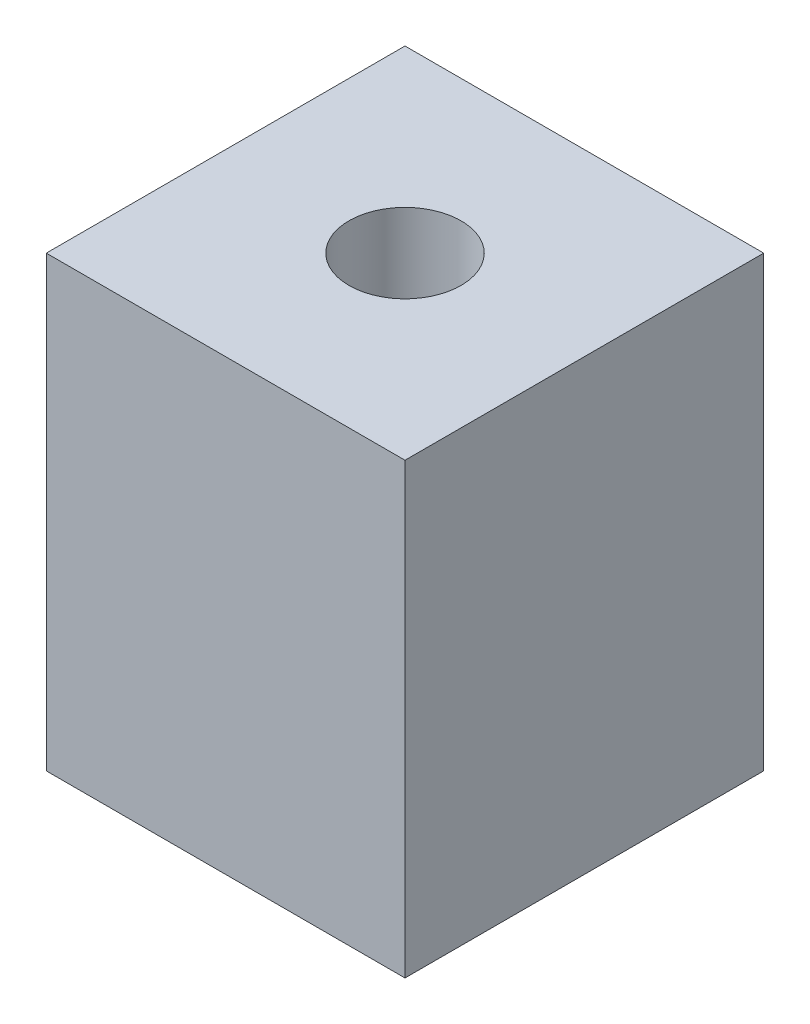
SolidWorks part; units mm, degrees
ref_plane "前基準面" through (0, 0, 0) normal (0, 0, 1) x (1, 0, 0)
ref_plane "上基準面" through (0, 0, 0) normal (0, 1, 0) x (1, 0, 0)
ref_plane "右基準面" through (0, 0, 0) normal (1, 0, 0) x (0, 0, -1)
sketch "草圖1" plane through (0, 0, 0) normal (0, 1, 0) x (1, 0, 0)
  circle A0 centre (0, 0) radius 6
  dimension "D1" = 12
extrude "填料-伸長1" add sketch "草圖1" along normal blind 40
sketch "草圖2" plane through (0, 40, 0) normal (0, 1, 0) x (1, 0, 0)
  circle A0 centre (0, 0) radius 5
  dimension "D1" = 10
extrude "除料-伸長2" cut sketch "草圖2" against normal blind 30
sketch "草圖3" plane through (0, 0, 0) normal (0, -1, 0) x (1, 0, 0)
  circle A0 centre (0, 0) radius 2.5
  dimension "D1" = 5
extrude "除料-伸長4" cut sketch "草圖3" against normal blind 10
sketch "草圖5" plane through (0, 0, 0) normal (0, 1, 0) x (1, 0, 0)
  circle A0 centre (0, 0) radius 6
extrude "伸長-薄件1" add sketch "草圖5" along normal blind 40 thin
sketch "草圖6" plane through (0, 40, 0) normal (0, 1, 0) x (1, 0, 0)
  line L1 (6, 6) -> (-6, 6)
  line L2 (6, 6) -> (6, -6)
  line L3 (6, -6) -> (-6, -6)
  line L4 (-6, 6) -> (-6, -6)
  line L5 (6, 6) -> (-6, -6) construction
  line L6 (6, -6) -> (-6, 6) construction
  point P0 (0, 0)
  dimension "D1" = 12
  dimension "D2" = 12
extrude "伸長-薄件2" add sketch "草圖6" against normal blind 40 thin
